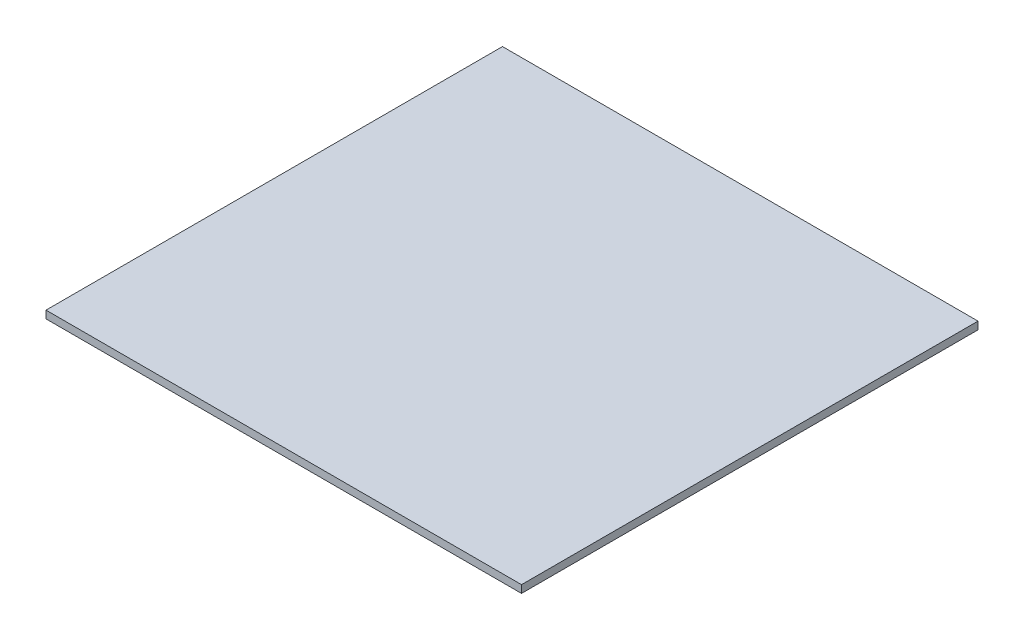
SolidWorks part; units mm, degrees
ref_plane "前基準面" through (0, 0, 0) normal (0, 0, 1) x (1, 0, 0)
ref_plane "上基準面" through (0, 0, 0) normal (0, 1, 0) x (1, 0, 0)
ref_plane "右基準面" through (0, 0, 0) normal (1, 0, 0) x (0, 0, -1)
sketch "草圖1" plane through (0, 0, 0) normal (0, 1, 0) x (1, 0, 0)
  line L1 (-56.25, 82.3621) -> (68.75, 82.3621)
  line L2 (-56.25, 82.3621) -> (-56.25, -37.6379)
  line L3 (-56.25, -37.6379) -> (68.75, -37.6379)
  line L4 (68.75, 82.3621) -> (68.75, -37.6379)
  dimension "D1" = 125
  dimension "D2" = 120
extrude "填料-伸長1" add sketch "草圖1" against normal blind 2
